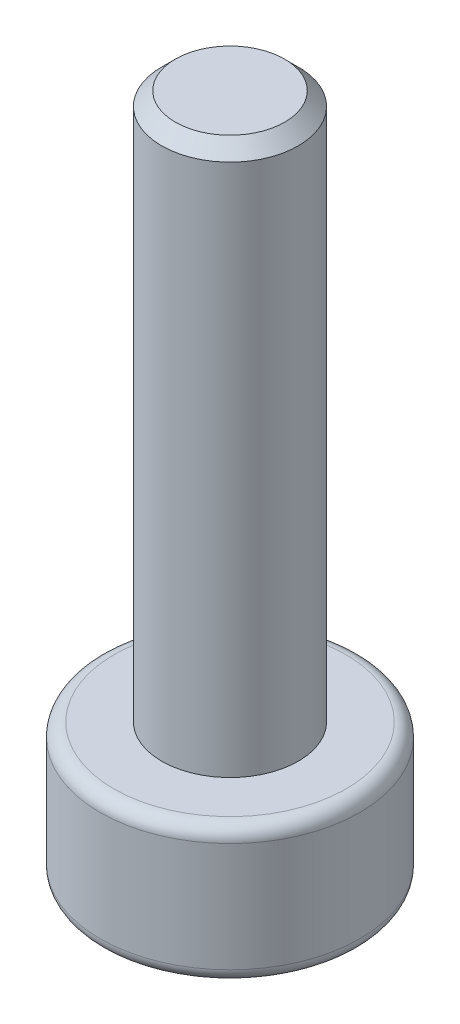
SolidWorks part; units mm, degrees
material "AISI 304"
ref_plane "前视基准面" through (0, 0, 0) normal (0, 0, 1) x (1, 0, 0)
ref_plane "上视基准面" through (0, 0, 0) normal (0, 1, 0) x (1, 0, 0)
ref_plane "右视基准面" through (0, 0, 0) normal (1, 0, 0) x (0, 0, -1)
sketch "草图1" plane through (0, 0, 0) normal (0, 1, 0) x (1, 0, 0)
  circle A0 centre (0, 0) radius 2.85
  dimension "D1" = 5.7
extrude "凸台-拉伸1" add sketch "草图1" along normal blind 3
sketch "草图2" plane through (0, 3, 0) normal (0, 1, 0) x (1, 0, 0)
  circle A0 centre (0, 0) radius 1.5
  dimension "D1" = 3
extrude "凸台-拉伸2" add sketch "草图2" along normal blind 12
sketch "草图3" plane through (0, 0, 0) normal (0, -1, 0) x (1, 0, 0)
  circle A0 centre (0, 0) radius 1.29
  dimension "D1" = 2.58
extrude "切除-拉伸1" cut sketch "草图3" against normal blind 1.3
fillet "圆角1" radius 0.3 2 edges at (0, 3, 2.85) (0, 0, 2.85)
chamfer "倒角1" distance 0.3 angle 45 1 edges at (0, 15, 1.5)
chamfer "倒角2" distance 0.15 angle 45 1 edges at (0, 0, -1.29)
